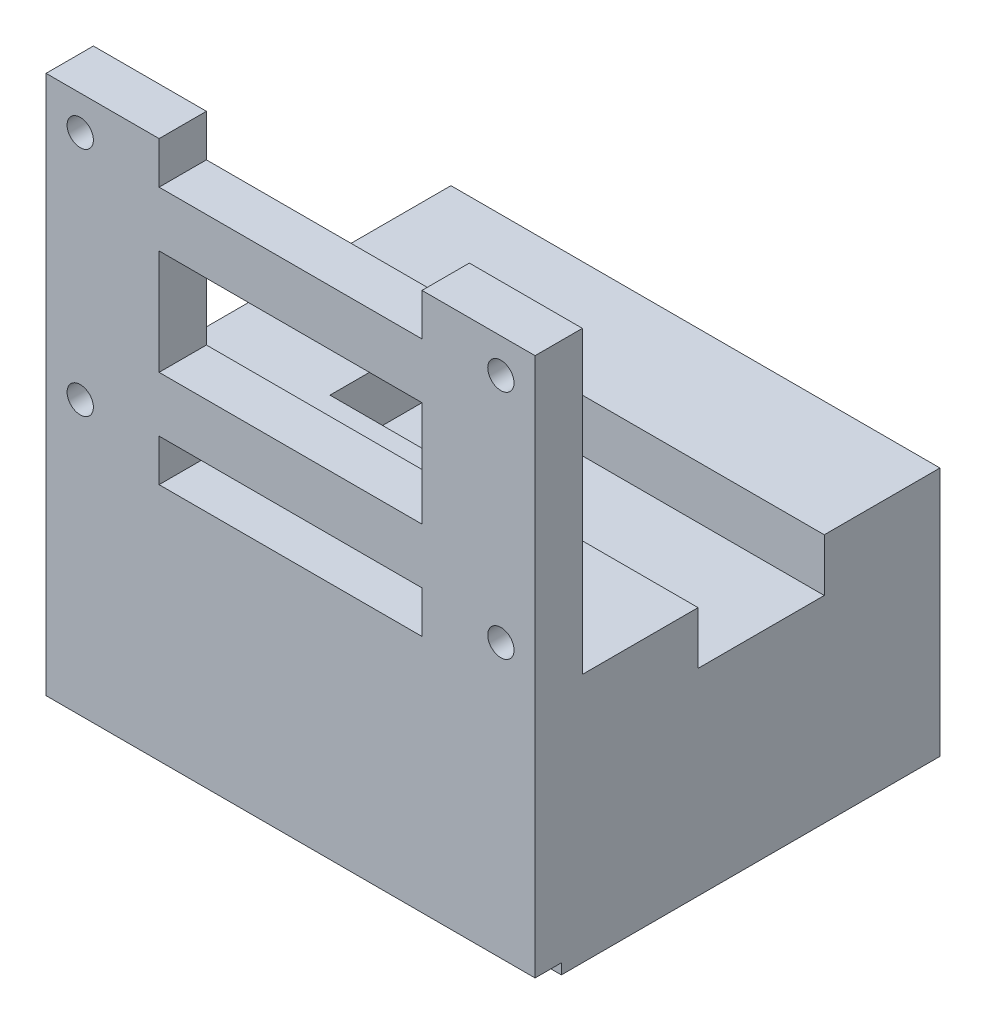
SolidWorks part; units mm, degrees
ref_plane "Front Plane" through (0, 0, 0) normal (0, 0, 1) x (1, 0, 0)
ref_plane "Top Plane" through (0, 0, 0) normal (0, 1, 0) x (1, 0, 0)
ref_plane "Right Plane" through (0, 0, 0) normal (1, 0, 0) x (0, 0, -1)
sketch "Sketch1" plane through (0, 0, 0) normal (0, 1, 0) x (1, 0, 0)
  line L1 (-23.25, -17) -> (23.25, -17)
  line L2 (-23.25, -17) -> (-23.25, 17)
  line L3 (-23.25, 17) -> (23.25, 17)
  line L4 (23.25, -17) -> (23.25, 17)
  line L5 (-23.25, -17) -> (23.25, 17) construction
  line L6 (-23.25, 17) -> (23.25, -17) construction
  point P0 (0, 0)
  dimension "D1" = 46.5
  dimension "D2" = 34
extrude "Boss-Extrude1" add sketch "Sketch1" along normal blind 13.75
sketch "Sketch2" plane through (0, 0, 17) normal (0, 0, 1) x (1, 0, 0)
  line L1 (-23.25, 0) -> (23.25, 0)
  line L2 (-23.25, 0) -> (-23.25, 42.25)
  line L3 (-23.25, 42.25) -> (23.25, 42.25)
  line L4 (23.25, 0) -> (23.25, 42.25)
  dimension "D1" = 46.5
  dimension "D2" = 42.25
extrude "Boss-Extrude2" add sketch "Sketch2" along normal blind 2
sketch "Sketch4" plane through (0, 13.75, 0) normal (0, 1, 0) x (1, 0, 0)
  line L0 (23.25, -17) -> (23.25, 17) construction
  line L1 (23.25, 6) -> (-11.75, 6)
  line L2 (23.25, 6) -> (23.25, -6)
  line L3 (23.25, -6) -> (-11.75, -6)
  line L4 (-11.75, 6) -> (-11.75, -6)
  line L5 (23.25, 17) -> (-23.25, 17) construction
  dimension "D1" = 35
  dimension "D2" = 12
  dimension "D3" = 11
extrude "Cut-Extrude2" cut sketch "Sketch4" against normal blind 5
sketch "Sketch6" plane through (0, 0, 0) normal (0, -1, 0) x (1, 0, 0)
  line L0 (16.25, -10) -> (16.25, 12)
  line L1 (23.25, -17) -> (-23.25, -17)
  line L2 (23.25, -17) -> (23.25, 19)
  line L3 (23.25, 19) -> (-23.25, 19)
  line L4 (-23.25, -17) -> (-23.25, 19)
  line L5 (16.25, 12) -> (-16.25, 12)
  line L6 (-16.25, -10) -> (-16.25, 12)
  line L7 (16.25, -10) -> (-16.25, -10)
  circle A0 centre (16.25, -10) radius 2
  circle A1 centre (16.25, 12) radius 2
  circle A2 centre (-16.25, -10) radius 2
  circle A3 centre (-16.25, 12) radius 2
  line M9 (23.25, -17) -> (23.25, 19)
  line M10 (23.25, 19) -> (-23.25, 19)
  line M11 (-23.25, 19) -> (-23.25, -17)
  line M12 (-23.25, -17) -> (23.25, -17)
  dimension "D2" = 4
  dimension "D3" = 4
  dimension "D4" = 4
  dimension "D5" = 4
  dimension "D1" = 7
extrude "Boss-Extrude3" add sketch "Sketch6" along normal blind 10 contours A3 L6 A2 L7 A0 L0 A1 L5 | A3 L5 A1 L0 A0 L7 A2 L6 M12 M9 M10 M11
ref_plane "Plane1" through (0, -9, 0) normal (0, -1, 0) x (-1, 0, 0)
sketch "Sketch8" plane through (0, -9, 0) normal (0, -1, 0) x (-1, 0, 0)
  line L1 (-23.25, -19) -> (23.25, -19)
  line L2 (-23.25, -19) -> (-23.25, -21.5)
  line L3 (-23.25, -21.5) -> (23.25, -21.5)
  line L4 (23.25, -19) -> (23.25, -21.5)
  dimension "D1" = 46.5
  dimension "D2" = 2.5
extrude "Boss-Extrude4" add sketch "Sketch8" against normal blind 51.25
sketch "Sketch3" plane through (0, 0, 19) normal (0, 0, 1) x (1, 0, 0)
  line L0 (-23.25, 28) -> (23.25, 28) construction
  line L1 (-12.5, 33) -> (12.5, 33)
  line L2 (-12.5, 33) -> (-12.5, 23)
  line L3 (-12.5, 23) -> (12.5, 23)
  line L4 (12.5, 33) -> (12.5, 23)
  line L5 (23.25, -10) -> (23.25, -9) construction
  line L6 (23.25, 42.25) -> (-23.25, 42.25) construction
  line L7 (-23.25, -9) -> (-23.25, -10) construction
  circle A0 centre (-20, 39) radius 1.25
  circle A2 centre (20, 39) radius 1.25
  circle A4 centre (20, 17) radius 1.25
  circle A5 centre (-20, 17) radius 1.25
  dimension "D1" = 2.5
  dimension "D11" = 2.5
  dimension "D2" = 10
  dimension "D3" = 25
  dimension "D4" = 5
  dimension "D5" = 10.75
  dimension "D6" = 14.25
  dimension "D7" = 3.25
  dimension "D8" = 3.25
  dimension "D9" = 3.25
  dimension "D10" = 3.25
extrude "Cut-Extrude1" cut sketch "Sketch3" against normal up to next and the other way blind 51
sketch "Sketch7" plane through (0, 0, 17) normal (0, 0, -1) x (-1, 0, 0)
  line L0 (23.25, 13.75) -> (-23.25, 13.75) construction
  line L1 (-12.5, 13.75) -> (12.5, 13.75)
  line L2 (-12.5, 13.75) -> (-12.5, 17.75)
  line L3 (-12.5, 17.75) -> (12.5, 17.75)
  line L4 (12.5, 13.75) -> (12.5, 17.75)
  line L5 (-23.25, 42.25) -> (23.25, 42.25) construction
  line L6 (-12.5, 42.25) -> (12.5, 42.25)
  line L7 (-12.5, 42.25) -> (-12.5, 38.25)
  line L8 (-12.5, 38.25) -> (12.5, 38.25)
  line L9 (12.5, 42.25) -> (12.5, 38.25)
  dimension "D1" = 4
  dimension "D2" = 4
extrude "Cut-Extrude3" cut sketch "Sketch7" against normal blind 10
